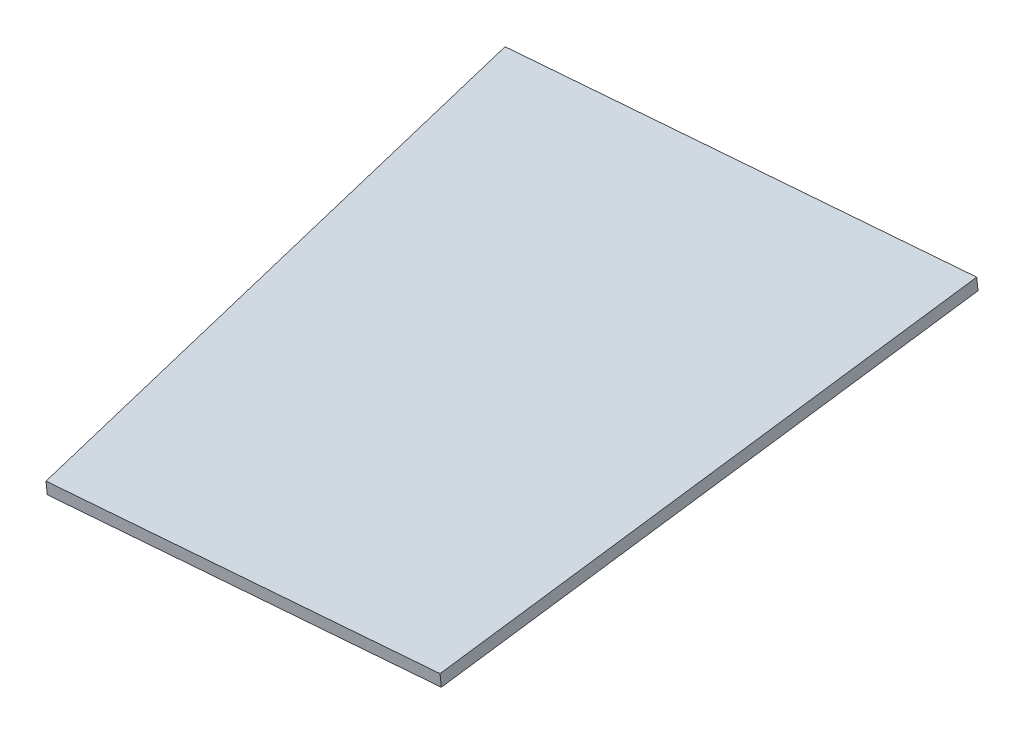
SolidWorks part; units mm, degrees
ref_plane "Front Plane" through (0, 0, 0) normal (0, 0, 1) x (1, 0, 0)
ref_plane "Top Plane" through (0, 0, 0) normal (0, 1, 0) x (1, 0, 0)
ref_plane "Right Plane" through (0, 0, 0) normal (1, 0, 0) x (0, 0, -1)
ref_plane "Pedlabox Floor Plane" through (4.4891, 322.0821, 37.0376) normal (-0.0138, -0.9934, -0.1142) x (-0.9999, 0.0139, 0.0005)
sketch "PedalBox Floor" plane through (4.4891, 322.0821, 37.0376) normal (-0.0138, -0.9934, -0.1142) x (-0.9999, 0.0139, 0.0005)
  line L0 (823.6975, -1109.2795) -> (811.3093, -1660.1683)
  line L1 (811.3093, -1660.1683) -> (1172.8621, -1691.8339)
  line L2 (1172.8621, -1691.8339) -> (1256.4242, -1147.1786)
  line L3 (1256.4242, -1147.1786) -> (823.6975, -1109.2795)
  line L4 (1227.0164, -1144.603) -> (853.1053, -1111.8551) construction
  line L9 (1173.6692, -1686.5734) -> (1286.2204, -952.9673) construction
  line L10 (828.1148, -912.8454) -> (811.429, -1654.8475) construction
  line L11 (1173.0032, -1691.8463) -> (811.1683, -1660.156) construction
extrude "Boss-Extrude1" add sketch "PedalBox Floor" along normal blind 12.7 contours L3 L0 L1 L2
